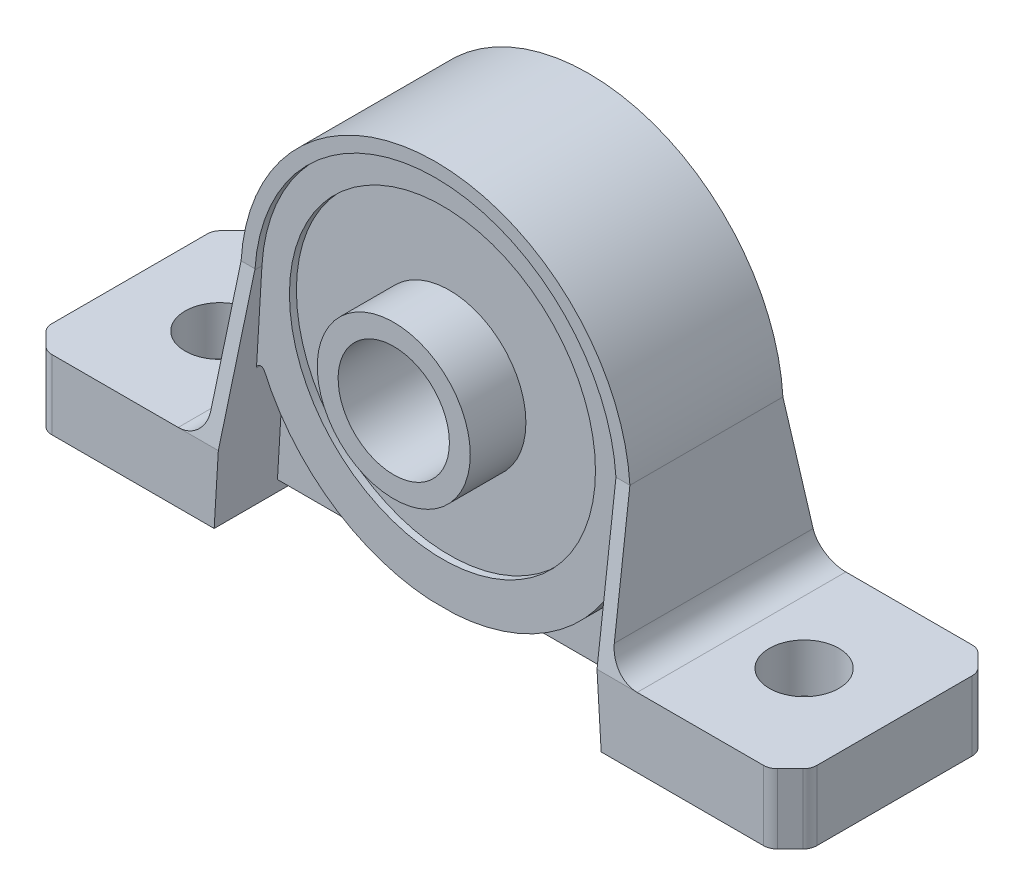
SolidWorks part; units mm, degrees
material "Aleación de zinc AC41A fundida"
ref_plane "Alzado" through (0, 0, 0) normal (0, 0, 1) x (1, 0, 0)
ref_plane "Planta" through (0, 0, 0) normal (0, 1, 0) x (1, 0, 0)
ref_plane "Vista lateral" through (0, 0, 0) normal (1, 0, 0) x (0, 0, -1)
sketch "Croquis1" plane through (0, 0, 0) normal (0, 0, 1) x (1, 0, 0)
  line L0 (0, -55) -> (0, 55) construction
  line L1 (27.5, -13.8902) -> (-27.5, -13.8902)
  line L2 (27.5, -13.8902) -> (27.5, -8.8902)
  line L4 (-27.5, -13.8902) -> (-27.5, -8.8902)
  line L7 (13.9749, 1.7438) -> (14.5, -7.01)
  line L8 (-13.9749, 1.7438) -> (-14.5, -7.01)
  line L9 (27.5, -8.8902) -> (16.4964, -8.8902)
  line L10 (-16.4964, -8.8902) -> (-27.5, -8.8902)
  arc A0 (13.9749, 1.7438) -> (-13.9749, 1.7438) centre (0, 0.9055) ccw
  arc A1 (-16.4964, -8.8902) -> (-14.5, -7.01) centre (-16.4964, -6.8902) ccw
  arc A2 (16.4964, -8.8902) -> (14.5, -7.01) centre (16.4964, -6.8902) cw
  circle A3 centre (0, 0.9055) radius 4
  point P0 (0, 0)
  dimension "D3" = 28
  dimension "D2" = 2
  dimension "D5" = 8
  dimension "D1" = 55
  dimension "D4" = 5
  dimension "D6" = 29
  dimension "D7" = 14.5
  dimension "D8" = 27.5
extrude "Saliente-Extruir1" add sketch "Croquis1" along normal blind 15
sketch "Croquis2" plane through (0, 0, 15) normal (0, 0, 1) x (1, 0, 0)
  circle A0 centre (0, 0.9055) radius 11
  dimension "D1" = 22
extrude "Cortar-Extruir1" cut sketch "Croquis2" against normal blind 3
sketch "Croquis3" plane through (0, 0, 12) normal (0, 0, 1) x (1, 0, 0)
  circle A0 centre (0, 0.9055) radius 5.5
  circle A1 centre (0, 0.9055) radius 4
  dimension "D1" = 11
extrude "Saliente-Extruir2" add sketch "Croquis3" along normal blind 4
sketch "Croquis4" plane through (0, 0, 0) normal (0, 1, 0) x (1, 0, 0)
  line L0 (-15.8376, 0) -> (15.8376, 0) construction
  line L1 (-27.5, -15) -> (-27.5, 0) construction
  line L2 (27.5, -15) -> (27.5, 0) construction
  circle A0 centre (-21, -7.5) radius 2.5
  circle A1 centre (21, -7.5) radius 2.5
  dimension "D1" = 5
  dimension "D2" = 7.5
  dimension "D3" = 6.5
  dimension "D4" = 6.5
extrude "Cortar-Extruir2" cut sketch "Croquis4" against normal through all both and the other way through all
ref_plane "Plano1" through (0, 0, 7.5) normal (0, 0, 1) x (1, 0, 0)
mirror "Simetría1" about plane through (0, 0, 7.5) normal (0, 0, 1) of "Cortar-Extruir1"
sketch "Croquis7" plane through (0, 0, 15) normal (0, 0, 1) x (1, 0, 0)
  line L0 (-13.9109, -13.8902) -> (-13.3702, -4.8769)
  line L1 (-27.5, -13.8902) -> (27.5, -13.8902) construction
  line L3 (13.9109, -13.8902) -> (13.3702, -4.8769)
  line L4 (14.5, -7.01) -> (13.9749, 1.7438) construction
  line L5 (-13.9749, 1.7438) -> (-14.5, -7.01) construction
  line L6 (-13.9109, -13.8902) -> (13.9109, -13.8902)
  arc A0 (-12.7966, -4.7732) -> (12.7966, -4.7732) centre (0, 0.9055) ccw
  arc A1 (13.9749, 1.7438) -> (-13.9749, 1.7438) centre (0, 0.9055) ccw construction
  arc A2 (13.3702, -4.8769) -> (12.7966, -4.7732) centre (13.0708, -4.8949) ccw
  arc A3 (-12.7966, -4.7732) -> (-13.3702, -4.8769) centre (-13.0708, -4.8949) ccw
  dimension "D3" = 0.3
  dimension "D1" = 1
  dimension "D2" = 1
extrude "Cortar-Extruir3" cut sketch "Croquis7" against normal blind 4.5
sketch "Croquis8" plane through (0, 0, 15) normal (0, 0, 1) x (1, 0, 0)
  line L0 (-13.9109, -13.8902) -> (-12.9767, 1.684)
  line L1 (13.9109, -13.8902) -> (12.9767, 1.684)
  line L2 (13.9109, -13.8902) -> (13.3702, -4.8769) construction
  line L3 (-13.3702, -4.8769) -> (-13.9109, -13.8902) construction
  line L4 (-13.9109, -13.8902) -> (13.9109, -13.8902)
  arc A0 (12.9767, 1.684) -> (-12.9767, 1.684) centre (0, 0.9055) ccw
  arc A1 (13.9749, 1.7438) -> (-13.9749, 1.7438) centre (0, 0.9055) ccw construction
  circle A2 centre (0, 0.9055) radius 5.5
  dimension "D1" = 1
extrude "Cortar-Extruir4" cut sketch "Croquis8" against normal blind 2.5
sketch "Croquis9" plane through (0, 0, 12.5) normal (0, 0, 1) x (1, 0, 0)
  line L0 (13.9109, -13.8902) -> (13.3702, -4.8769) construction
  line L1 (-13.9109, -13.8902) -> (13.9109, -13.8902) construction
  line L2 (-13.3702, -4.8769) -> (-13.9109, -13.8902) construction
  line L3 (13.9109, -13.8902) -> (13.8614, -13.0646)
  line L4 (-13.9109, -13.8902) -> (13.9109, -13.8902)
  line L5 (-13.8614, -13.0646) -> (-13.9109, -13.8902)
  line L6 (-13.8614, -13.0646) -> (13.8614, -13.0646)
extrude "Cortar-Extruir5" cut sketch "Croquis9" against normal through all both and the other way through all
sketch "Croquis10" plane through (27.5, 0, 0) normal (1, 0, 0) x (0, 0, -1)
  line L0 (-15, -8.8902) -> (-13, 1.7438)
  line L1 (-13, 1.7438) -> (-13, 14.9055)
  line L2 (0, 14.9055) -> (-15, 14.9055) construction
  line L3 (-13, 14.9055) -> (-2, 14.9055)
  line L4 (-2, 14.9055) -> (-2, 1.7438)
  line L5 (-2, 1.7438) -> (0, -8.8902)
  line L6 (0, 15.8376) -> (0, -15.8376) construction
  line L7 (-15, -8.8902) -> (0, -8.8902) construction
  line L8 (-15, -7.01) -> (-15, 1.7438) construction
  line L9 (-15, 1.7438) -> (0, 1.7438) construction
  line L10 (-15, -8.8902) -> (-15, 15.9897)
  line L11 (-15, 15.9897) -> (-13, 14.9055)
  line L12 (-2, 14.9055) -> (0, 15.9897)
  line L13 (0, 15.9897) -> (0, -8.8902)
  dimension "D1" = 2
  dimension "D2" = 2
extrude "Cortar-Extruir6" cut sketch "Croquis10" against normal up to surface (55.001 mm away) contours L11 L10 L0 L1 | L12 L13 L5 L4
sketch "Croquis11" plane through (0, -13.8902, 0) normal (0, -1, 0) x (1, 0, 0)
  line L0 (-26.2929, 14.7071) -> (-27.2071, 13.7929)
  line L2 (-33.9703, 16.2695) -> (-33.9703, -5.5307)
  line L3 (-27.5, 15) -> (-13.9109, 15) construction
  line L23 (-27.5, 15) -> (-27.5, 0) construction
  line L37 (15.8376, 0) -> (-15.8376, 0) construction
  line L39 (-26.2929, 0.2929) -> (-27.2071, 1.2071)
  line L40 (-25.5858, 15) -> (-15.5405, 15)
  line L44 (-27.5, 13.0858) -> (-27.5, 1.9142)
  line L45 (-33.9703, 16.2695) -> (-15.5405, 16.2695)
  line L46 (-15.5405, 16.2695) -> (-15.5405, 15)
  line L47 (-33.9703, -5.5307) -> (-15.5405, -5.5307)
  line L48 (-25.5858, 0) -> (-15.5405, 0)
  line L49 (-15.5405, 0) -> (-15.5405, -5.5307)
  arc A12 (-26.2929, 0.2929) -> (-25.5858, 0) centre (-25.5858, 1) ccw
  arc A13 (-27.2071, 1.2071) -> (-27.5, 1.9142) centre (-26.5, 1.9142) cw
  arc A14 (-27.2071, 13.7929) -> (-27.5, 13.0858) centre (-26.5, 13.0858) ccw
  arc A15 (-26.2929, 14.7071) -> (-25.5858, 15) centre (-25.5858, 14) cw
  point P15 (-26, 0)
  point P21 (-27.5, 1.5)
  point P24 (-27.5, 13.5)
  point P27 (-26, 15)
  dimension "D1" = 1
extrude "Cortar-Extruir7" cut sketch "Croquis11" against normal up to surface (5 mm away) up to face at (-18.5, -8.8902, 7.5)
sketch "Croquis12" plane through (0, -13.8902, 0) normal (0, -1, 0) x (1, 0, 0)
  line L0 (-25.5858, 15) -> (-13.9109, 15) construction
  line L1 (-25, 13.5) -> (-16.4109, 13.5)
  line L2 (-26, 12.5) -> (-26, 2.5)
  line L3 (-25, 1.5) -> (-16.4109, 1.5)
  line L4 (-15.4109, 12.5) -> (-15.4109, 2.5)
  line L9 (-27.5, 13.0858) -> (-27.5, 1.9142) construction
  line L10 (-13.9109, 0) -> (-13.9109, 15) construction
  line L11 (15.8376, 0) -> (-15.8376, 0) construction
  arc A0 (-16.4109, 13.5) -> (-15.4109, 12.5) centre (-16.4109, 12.5) cw
  arc A1 (-15.4109, 2.5) -> (-16.4109, 1.5) centre (-16.4109, 2.5) cw
  arc A2 (-25, 1.5) -> (-26, 2.5) centre (-25, 2.5) cw
  arc A3 (-26, 12.5) -> (-25, 13.5) centre (-25, 12.5) cw
  dimension "D5" = 1
  dimension "D1" = 1.5
  dimension "D2" = 1.5
  dimension "D3" = 1.5
  dimension "D4" = 1.5
extrude "Cortar-Extruir8" cut sketch "Croquis12" against normal blind 1.5
mirror "Simetría2" about plane through (0, 0, 0) normal (1, 0, 0) of "Cortar-Extruir8", "Cortar-Extruir7"
mirror "Simetría4" about plane through (0, 0, 7.5) normal (0, 0, 1) of "Cortar-Extruir3", "Cortar-Extruir4"
sketch "Croquis13" plane through (0, 0, 3) normal (0, 0, -1) x (-1, 0, 0)
  circle A0 centre (0, 0.9055) radius 5.5
  circle A1 centre (0, 0.9055) radius 4
extrude "Saliente-Extruir3" add sketch "Croquis13" along normal up to surface (1 mm away) up to face at (0, 8.0747, 2)
scale "Scale1" scale about centroid uniform scaling yes scale factor 2
